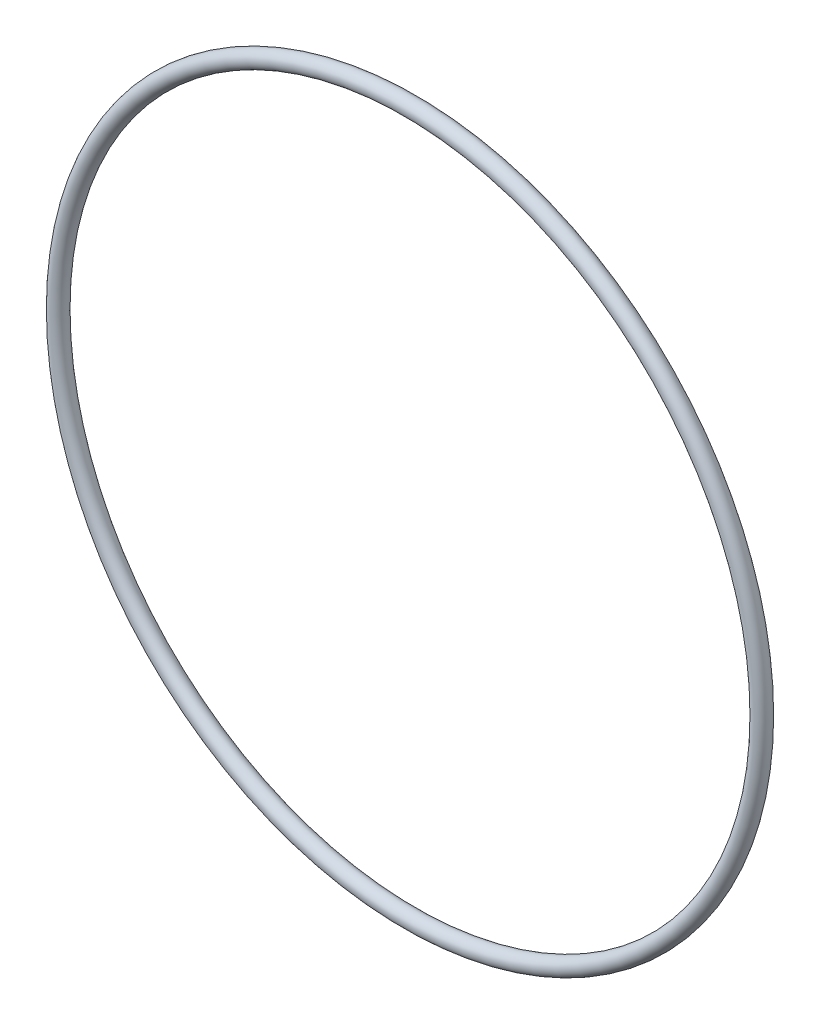
SolidWorks part; units mm, degrees
material "Rubber"
ref_plane "Front Plane" through (0, 0, 0) normal (0, 0, 1) x (1, 0, 0)
ref_plane "Top Plane" through (0, 0, 0) normal (0, 1, 0) x (1, 0, 0)
ref_plane "Right Plane" through (0, 0, 0) normal (1, 0, 0) x (0, 0, -1)
sketch "Sketch1" plane through (0, 0, 0) normal (0, 0, 1) x (1, 0, 0)
  circle A0 centre (0, 0) radius 55
  dimension "D1" = 110
sketch "Sketch2" plane through (0, 0, 0) normal (0, 1, 0) x (1, 0, 0)
  line L0 (-55, 0) -> (55, 0) construction
  circle A0 centre (-55, 0) radius 1.31
  dimension "D2" = 2.62
  dimension "D1" = 55
sweep "Sweep1" add profiles "Sketch2" path "Sketch1"
